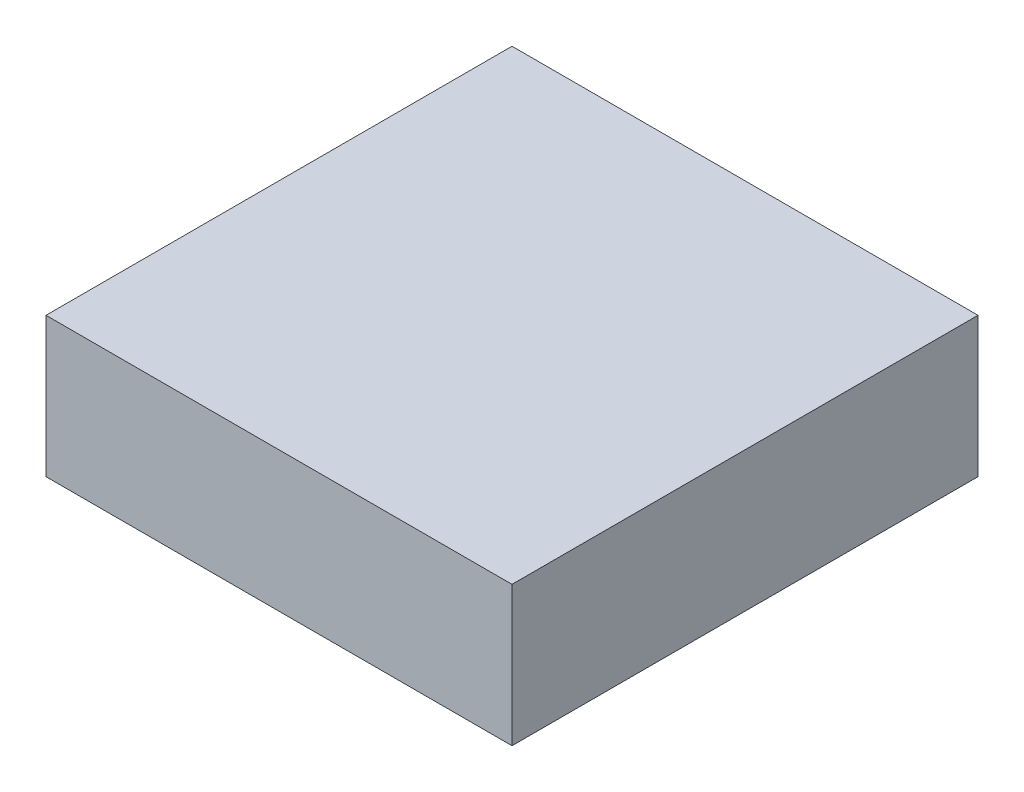
SolidWorks part; units mm, degrees
ref_plane "Alzado" through (0, 0, 0) normal (0, 0, 1) x (1, 0, 0)
ref_plane "Planta" through (0, 0, 0) normal (0, 1, 0) x (1, 0, 0)
ref_plane "Vista lateral" through (0, 0, 0) normal (1, 0, 0) x (0, 0, -1)
sketch "Croquis1" plane through (0, 0, 0) normal (0, 1, 0) x (1, 0, 0)
  line L1 (-250, -250) -> (250, -250)
  line L2 (-250, -250) -> (-250, 250)
  line L3 (-250, 250) -> (250, 250)
  line L4 (250, -250) -> (250, 250)
  line L5 (-250, -250) -> (250, 250) construction
  line L6 (-250, 250) -> (250, -250) construction
  point P0 (0, 0)
  dimension "D1" = 500
  dimension "D2" = 500
extrude "Saliente-Extruir1" add sketch "Croquis1" along normal blind 150
